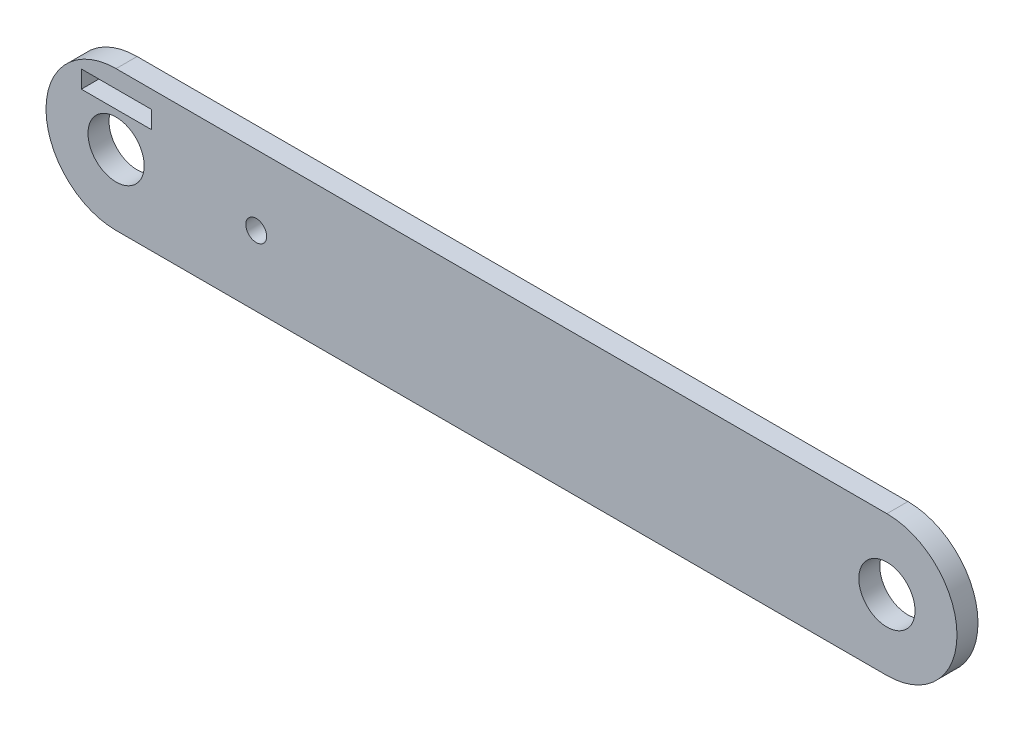
SolidWorks part; units mm, degrees
ref_plane "Front Plane" through (0, 0, 0) normal (0, 0, 1) x (1, 0, 0)
ref_plane "Top Plane" through (0, 0, 0) normal (0, 1, 0) x (1, 0, 0)
ref_plane "Right Plane" through (0, 0, 0) normal (1, 0, 0) x (0, 0, -1)
sketch "Sketch1" plane through (0, 0, 0) normal (0, 0, 1) x (1, 0, 0)
  line L0 (0, 10) -> (110, 10)
  line L1 (0, -10) -> (110, -10)
  circle A0 centre (0, 0) radius 10
  circle A2 centre (0, 0) radius 4.01
  circle A3 centre (110, 0) radius 4.01
  circle A4 centre (110, 0) radius 10
  dimension "D1" = 20
  dimension "D2" = 20
  dimension "D4" = 8.02
  dimension "D5" = 8.02
  dimension "D3" = 110
  dimension "D6" = 110
extrude "Boss-Extrude1" add sketch "Sketch1" along normal blind 3
sketch "Sketch2" plane through (0, 0, 0) normal (0, 0, -1) x (-1, 0, 0)
  circle A2 centre (-20, 0) radius 1.49
  dimension "D1" = 20
  dimension "D2" = 2.98
sketch "Sketch4" plane through (0, 0, 0) normal (0, 0, -1) x (-1, 0, 0)
  line L0 (4.9531, 4.9852) -> (-5.0469, 4.9852)
  line L2 (4.9531, 4.9852) -> (-5.0469, 4.9852)
  line L3 (4.9531, 4.9852) -> (4.9531, 7.4852)
  line L4 (4.9531, 7.4852) -> (-5.0469, 7.4852)
  line L5 (-5.0469, 4.9852) -> (-5.0469, 7.4852)
  dimension "D1" = 2.5
  dimension "D2" = 10
extrude "Cut-Extrude2" cut sketch "Sketch4" against normal up to next contours L5 L0 L3 L4
extrude "Cut-Extrude3" cut sketch "Sketch2" against normal blind 10
